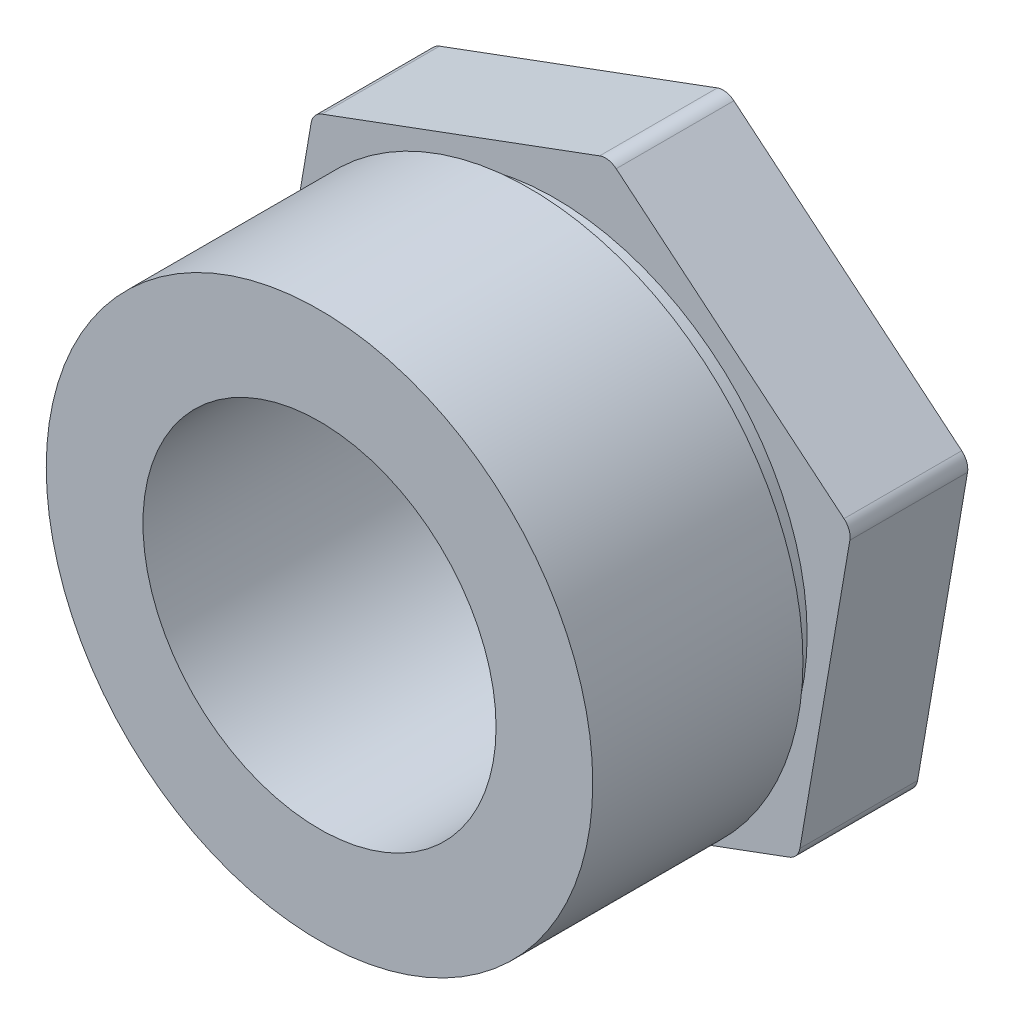
SolidWorks part; units mm, degrees
ref_plane "Front Plane" through (0, 0, 0) normal (0, 0, 1) x (1, 0, 0)
ref_plane "Top Plane" through (0, 0, 0) normal (0, 1, 0) x (1, 0, 0)
ref_plane "Right Plane" through (0, 0, 0) normal (1, 0, 0) x (0, 0, -1)
sketch "Sketch1" plane through (0, 0, 0) normal (0, 0, 1) x (1, 0, 0)
  circle A0 centre (0, 0) radius 32.5
  dimension "D1" = 65
extrude "Boss-Extrude1" add sketch "Sketch1" along normal blind 42
cosmetic thread "Cosmetic Thread1" parameters "D1"=25, "D2"=59.61
sketch "Sketch2" plane through (0, 0, 42) normal (0, 0, 1) x (1, 0, 0)
  circle A0 centre (0, 0) radius 30
  circle A2 centre (0, 0) radius 32.5
  circle A3 centre (0, 0) radius 32.5
  dimension "D1" = 0
extrude "Cut-Extrude1" cut sketch "Sketch2" along normal blind 3 from offset 28 offset against normal yes
sketch "Sketch3" plane through (0, 0, 0) normal (0, 0, -1) x (-1, 0, 0)
  line L1 (-35.2699, 13.4301) -> (-28.9414, -23.5602)
  line L2 (-28.9414, -23.5602) -> (6.2574, -36.5747)
  line L3 (6.2574, -36.5747) -> (35.1277, -12.5989)
  line L4 (35.1277, -12.5989) -> (28.7992, 24.3914)
  line L5 (28.7992, 24.3914) -> (-6.3996, 37.4059)
  line L6 (-6.3996, 37.4059) -> (-35.2699, 13.4301)
  circle A0 centre (-0.0711, 0.4156) radius 32.5 construction
  dimension "D1" = 65
extrude "Boss-Extrude2" add sketch "Sketch3" against normal blind 14
fillet "Fillet1" radius 2 6 edges at (-6.2574, -36.5747, 7) (-35.1277, -12.5989, 7) (-28.7992, 24.3914, 7) (6.3996, 37.4059, 7) (28.9414, -23.5602, 7) (35.2699, 13.4301, 7)
sketch "Sketch4" plane through (0, 0, 42) normal (0, 0, 1) x (1, 0, 0)
  circle A0 centre (0, 0) radius 21
extrude "Cut-Extrude2" cut sketch "Sketch4" against normal through all
